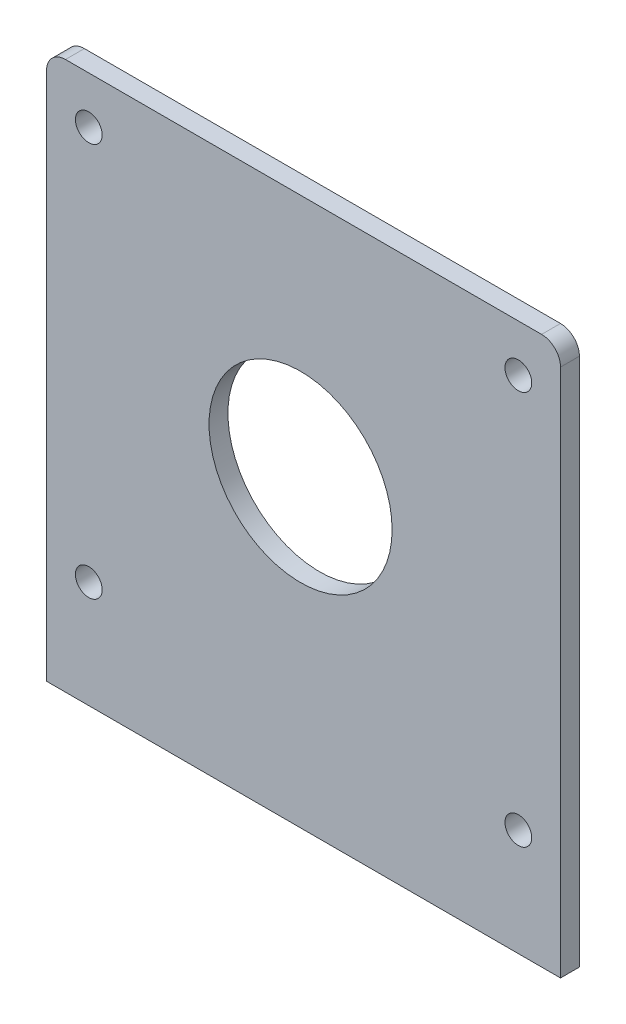
SolidWorks part; units mm, degrees
material "ASTM A36 Steel"
ref_plane "X-Y Datum" through (0, 0, 0) normal (0, 0, 1) x (1, 0, 0)
ref_plane "X-Z Datum" through (0, 0, 0) normal (0, 1, 0) x (1, 0, 0)
ref_plane "Y-Z Datum" through (0, 0, 0) normal (1, 0, 0) x (0, 0, -1)
sketch "Sketch2" plane through (0, 0, 0) normal (0, 0, 1) x (1, 0, 0)
  line L0 (43.18, 42.8625) -> (-43.18, 42.8625)
  line L2 (-43.18, 42.8625) -> (-43.18, -42.8625)
  line L4 (-43.18, 42.8625) -> (0, 0) construction
  line L5 (-43.18, -42.8625) -> (0, 0) construction
  line L6 (-43.18, -42.8625) -> (43.18, -42.8625)
  line L7 (43.18, -42.8625) -> (43.18, 42.8625)
  line L8 (0, 0) -> (43.18, -42.8625) construction
  line L9 (0, 0) -> (43.18, 42.8625) construction
  dimension "D1" = 86.36
  dimension "D3" = 85.725
extrude "Boss-Extrude1" add sketch "Sketch2" along normal mid plane 3.175
sketch "Sketch3" plane through (0, 0, 1.5875) normal (0, 0, 1) x (1, 0, 0)
  circle A0 centre (-0.5, 1.8625) radius 15 construction
  circle A3 centre (-36.0914, -31.2289) radius 3.025 construction
  circle A4 centre (36.0914, -31.2289) radius 3.025 construction
  circle A5 centre (-36.0914, 34.9539) radius 3.025 construction
  circle A6 centre (36.0914, 34.9539) radius 3.025 construction
  circle A7 centre (-36.0914, -31.2289) radius 3.025 construction
  circle A8 centre (36.0914, -31.2289) radius 3.025 construction
  circle A9 centre (-36.0914, 34.9539) radius 3.025 construction
  circle A10 centre (36.0914, 34.9539) radius 3.025 construction
  circle A11 centre (-0.5, 1.8625) radius 15.381
  circle A12 centre (-0.5, 1.8625) radius 15 construction
  point P3 (36.0914, -31.2289)
  point P4 (-36.0914, -31.2289)
  point P6 (-36.0914, 34.9539)
  point P8 (36.0914, 34.9539)
  point P24 (-0.5, 1.8625)
  dimension "D1" = 30.762
  dimension "D2" = 30
  dimension "D3" = 0.381
extrude "Cut-Extrude1" cut sketch "Sketch3" against normal through all
hole_wizard "M4 Clearance Hole1" positions "3DSketch1" profile "Sketch4" hole size "M4" standard "ANSI Metric" end condition through all
sketch3d "3DSketch1"
  point P0 (36.0914, 34.9539, 1.5875)
  point P3 (36.0914, -31.2289, 1.5875)
  point P6 (-36.0914, 34.9539, 1.5875)
  point P9 (-36.0914, -31.2289, 1.5875)
sketch "Sketch4" plane through (36.0914, 34.9539, 1.5875) normal (1, 0, 0) x (0, -1, 0)
  line L0 (0, 0) -> (0, 3.175)
  line L1 (0, 3.175) -> (2.25, 3.175)
  line L2 (2.25, 3.175) -> (2.25, 0)
  line L5 (2.25, 0) -> (0, 0)
  line L11 (0, -6.35) -> (0, 107.95) construction
  dimension "Thru Hole Dia." = 4.5
  dimension "Thru Hole Depth" = 3.175
sketch "Sketch5" plane through (0, 0, 1.5875) normal (0, 0, 1) x (1, 0, 0)
  line L0 (-43.18, 42.8625) -> (-43.18, -42.8625) construction
  line L1 (43.18, -42.8625) -> (-43.18, -42.8625)
  line L2 (43.18, -42.8625) -> (43.18, -49.2125)
  line L3 (43.18, -49.2125) -> (-43.18, -49.2125)
  line L4 (-43.18, -42.8625) -> (-43.18, -49.2125)
  dimension "D1" = 6.35
extrude "Boss-Extrude2" add sketch "Sketch5" against normal blind 3.175
fillet "Fillet1" radius 3.175 2 edges at (-43.18, 42.8625, 0) (43.18, 42.8625, 0)
